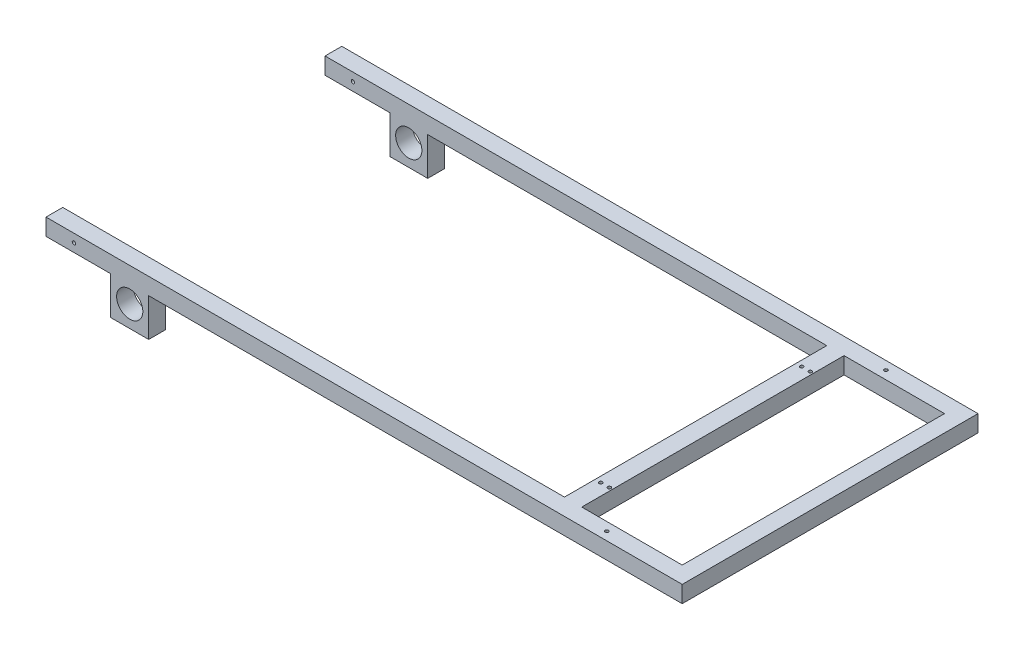
SolidWorks part; units mm, degrees
ref_plane "前视基准面" through (0, 0, 0) normal (0, 0, 1) x (1, 0, 0)
ref_plane "上视基准面" through (0, 0, 0) normal (0, 1, 0) x (1, 0, 0)
ref_plane "右视基准面" through (0, 0, 0) normal (1, 0, 0) x (0, 0, -1)
sketch "草图1" plane through (0, 0, 0) normal (0, 1, 0) x (1, 0, 0)
  line L1 (-990, 265) -> (990, 265)
  line L2 (-990, 265) -> (-990, -265)
  line L3 (-990, -265) -> (990, -265)
  line L4 (990, 265) -> (990, -265)
  line L5 (-990, 265) -> (990, -265) construction
  line L6 (-990, -265) -> (990, 265) construction
  line L7 (-960, 235) -> (960, 235)
  line L8 (-960, 235) -> (-960, -235)
  line L9 (-960, -235) -> (960, -235)
  line L10 (960, 235) -> (960, -235)
  line L11 (-960, 235) -> (960, -235) construction
  line L12 (-960, -235) -> (960, 235) construction
  point P0 (0, 0)
  point P6 (0, 0)
  dimension "D1" = 1980
  dimension "D2" = 530
  dimension "D3" = 30
  dimension "D4" = 30
extrude "凸台-拉伸1" add sketch "草图1" along normal blind 30
sketch "草图2" plane through (0, 0, 0) normal (0, -1, 0) x (1, 0, 0)
  line L0 (0, 439.6423) -> (0, -491.4203) construction
  line L1 (-990, 265) -> (990, 265) construction
  line L2 (-34, 265) -> (34, 265)
  line L3 (-34, 265) -> (-34, 235)
  line L4 (-34, 235) -> (34, 235)
  line L5 (34, 265) -> (34, 235)
  line L6 (-960, 235) -> (960, 235) construction
  line L7 (960, -235) -> (-960, -235) construction
  line L8 (-34, -235) -> (34, -235)
  line L9 (-34, -235) -> (-34, -265)
  line L10 (-34, -265) -> (34, -265)
  line L11 (34, -235) -> (34, -265)
  line L12 (990, -265) -> (-990, -265) construction
  dimension "D1" = 68
  dimension "D2" = 34
  dimension "D3" = 68
  dimension "D4" = 34
extrude "凸台-拉伸2" add sketch "草图2" along normal blind 68
sketch "草图3" plane through (0, 0, 265) normal (0, 0, 1) x (1, 0, 0)
  line L0 (34, -68) -> (-34, -68) construction
  circle A0 centre (0, -30) radius 23.5
  dimension "D1" = 47
  dimension "D2" = 38
extrude "切除-拉伸1" cut sketch "草图3" against normal through all
sketch "草图4" plane through (0, 30, 0) normal (0, 1, 0) x (1, 0, 0)
  line L0 (960, 235) -> (-960, 235) construction
  line L1 (749, 235) -> (780, 235)
  line L2 (749, 235) -> (749, -235)
  line L3 (749, -235) -> (780, -235)
  line L4 (780, 235) -> (780, -235)
  line L5 (-960, -235) -> (960, -235) construction
  line L6 (960, -235) -> (960, 235) construction
  dimension "D1" = 31
  dimension "D2" = 180
extrude "凸台-拉伸3" add sketch "草图4" against normal up to surface (30 mm away) up to face at (504.5, 0, 0)
sketch "草图5" plane through (0, 30, 0) normal (0, 1, 0) x (1, 0, 0)
  line L0 (759, 180) -> (774.5, 180) construction
  line L1 (749, 235) -> (749, -235) construction
  line L2 (780, -235) -> (780, 235) construction
  line L3 (-200.9007, 0) -> (293.2172, 0) construction
  circle A0 centre (759, 180) radius 3
  circle A1 centre (774.5, 180) radius 3
  circle A2 centre (759, -180) radius 3
  circle A3 centre (774.5, -180) radius 3
  dimension "D1" = 6
  dimension "D2" = 6
  dimension "D3" = 10
  dimension "D4" = 5.5
  dimension "D5" = 180
extrude "切除-拉伸2" cut sketch "草图5" against normal through all
sketch "草图6" plane through (0, 30, 0) normal (0, 1, 0) x (1, 0, 0)
  line L0 (900.6933, -265) -> (900.6933, -235) construction
  line L1 (-990, -265) -> (990, -265) construction
  line L2 (780, -235) -> (960, -235) construction
  line L3 (990, -265) -> (990, 265) construction
  circle A0 centre (840, -250) radius 3
  dimension "D1" = 6
  dimension "D2" = 150
extrude "切除-拉伸3" cut sketch "草图6" against normal through all and the other way through all
mirror "镜向1" about plane through (0, 0, 0) normal (0, 0, 1) of "切除-拉伸3"
sketch "草图7" plane through (0, 0, 265) normal (0, 0, 1) x (1, 0, 0)
  line L0 (0, 279.6967) -> (0, -357.4445) construction
  line L1 (-150, 30) -> (-150, 0)
  line L2 (-990, 30) -> (990, 30) construction
  line L3 (-990, 0) -> (-34, 0) construction
  line L4 (-150, 30) -> (-1033.3995, 30)
  line L5 (-1033.3995, 30) -> (-1033.3995, 0)
  line L6 (-1033.3995, 0) -> (-150, 0)
  point P9 (-150, 15)
  dimension "D1" = 150
extrude "切除-拉伸4" cut sketch "草图7" against normal through all
sketch "草图8" plane through (0, 0, 265) normal (0, 0, 1) x (1, 0, 0)
  line L0 (-150, 0) -> (-150, 30) construction
  circle A0 centre (-100, 15) radius 3
  dimension "D2" = 6
  dimension "D1" = 50
extrude "切除-拉伸5" cut sketch "草图8" against normal through all
